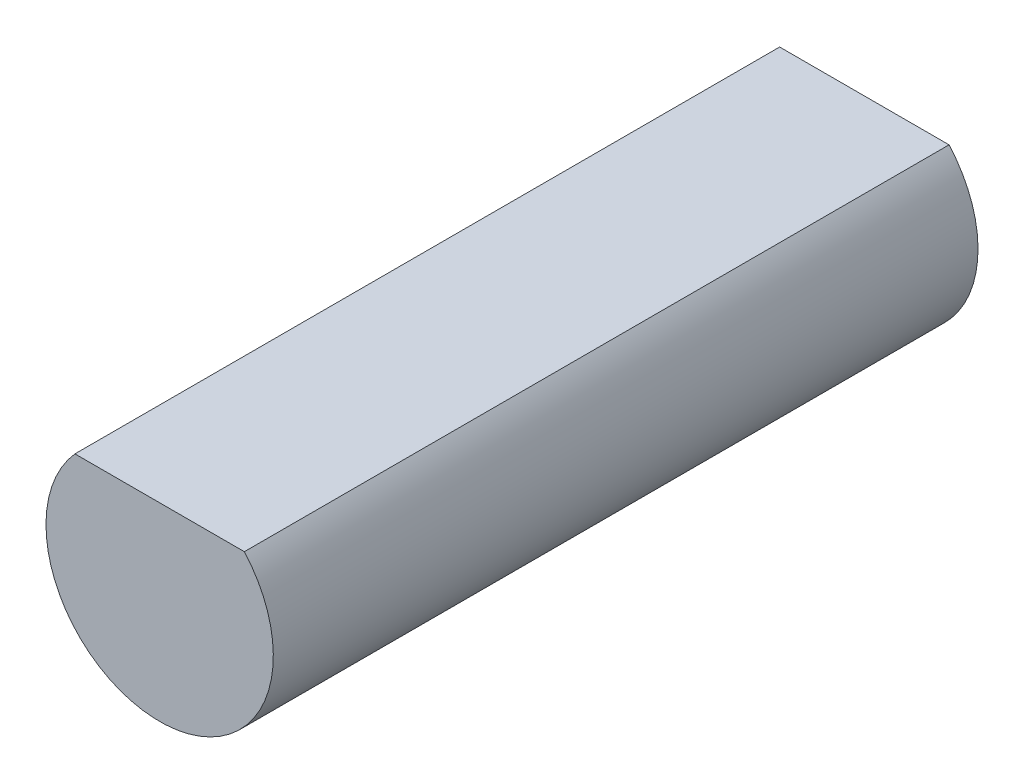
SolidWorks part; units mm, degrees
ref_plane "Front Plane" through (0, 0, 0) normal (0, 0, 1) x (1, 0, 0)
ref_plane "Top Plane" through (0, 0, 0) normal (0, 1, 0) x (1, 0, 0)
ref_plane "Right Plane" through (0, 0, 0) normal (1, 0, 0) x (0, 0, -1)
sketch "Sketch1" plane through (0, 0, 0) normal (0, 0, 1) x (1, 0, 0)
  line L0 (-1.5, -1.5) -> (1.5, -1.5) construction
  line L1 (-1.118, 1) -> (1.118, 1)
  arc A0 (-1.118, 1) -> (1.118, 1) centre (0, 0) ccw
  point P6 (0, -1.5)
  dimension "D1" = 3
  dimension "D2" = 2.5
extrude "Boss-Extrude1" add sketch "Sketch1" along normal blind 9.3
